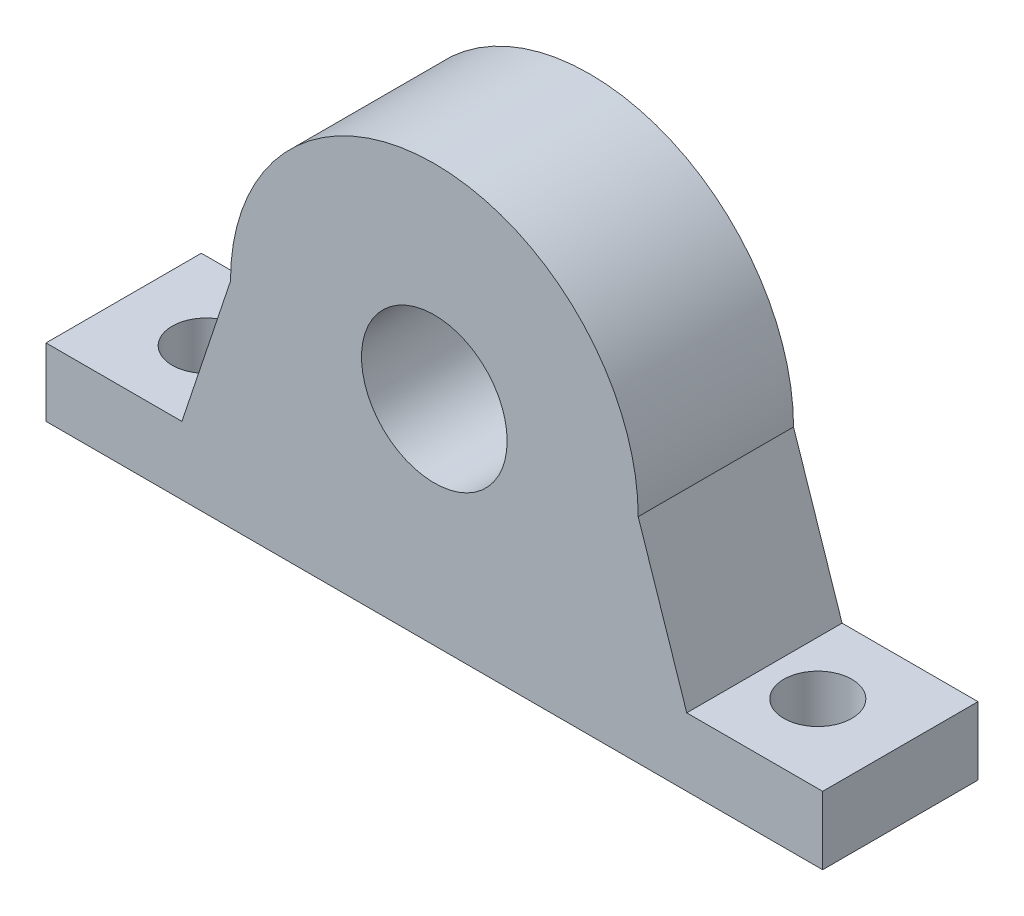
SolidWorks part; units mm, degrees
ref_plane "前视基准面" through (0, 0, 0) normal (0, 0, 1) x (1, 0, 0)
ref_plane "上视基准面" through (0, 0, 0) normal (0, 1, 0) x (1, 0, 0)
ref_plane "右视基准面" through (0, 0, 0) normal (1, 0, 0) x (0, 0, -1)
sketch "草图1" plane through (0, 0, 0) normal (0, 0, 1) x (1, 0, 0)
  line L0 (-21, 0) -> (-26, -15)
  line L1 (-26, -15) -> (-40, -15)
  line L2 (-40, -15) -> (-40, -22)
  line L3 (-40, -22) -> (40, -22)
  line L4 (40, -22) -> (40, -15)
  line L5 (40, -15) -> (26, -15)
  line L6 (26, -15) -> (21, 0)
  line L7 (0, -22) -> (0, 23.7683) construction
  circle A0 centre (0, 0) radius 7.5
  arc A1 (-21, 0) -> (21, 0) centre (0, 0) cw
  point P13 (0, 21)
  point P14 (24.0451, -15)
  point P15 (20.4217, -4.8944)
  point P16 (0, 0)
  dimension "D1" = 15
  dimension "D5" = 43
  dimension "D2" = 80
  dimension "D3" = 22
  dimension "D4" = 7
  dimension "D6" = 14
extrude "凸台-拉伸1" add sketch "草图1" along normal blind 16
sketch "草图3" plane through (0, -15, 0) normal (0, 1, 0) x (1, 0, 0)
  line L0 (-40, -8) -> (40, -8) construction
  line L1 (-40, -16) -> (-40, 0) construction
  line L2 (40, -16) -> (40, 0) construction
  line L3 (0, -16) -> (0, 0) construction
  line L4 (-21, -16) -> (21, -16) construction
  circle A0 centre (-31.5, -8) radius 3.5
  circle A1 centre (31.5, -8) radius 3.5
  dimension "D1" = 7
  dimension "D2" = 63
extrude "切除-拉伸1" cut sketch "草图3" against normal through all
